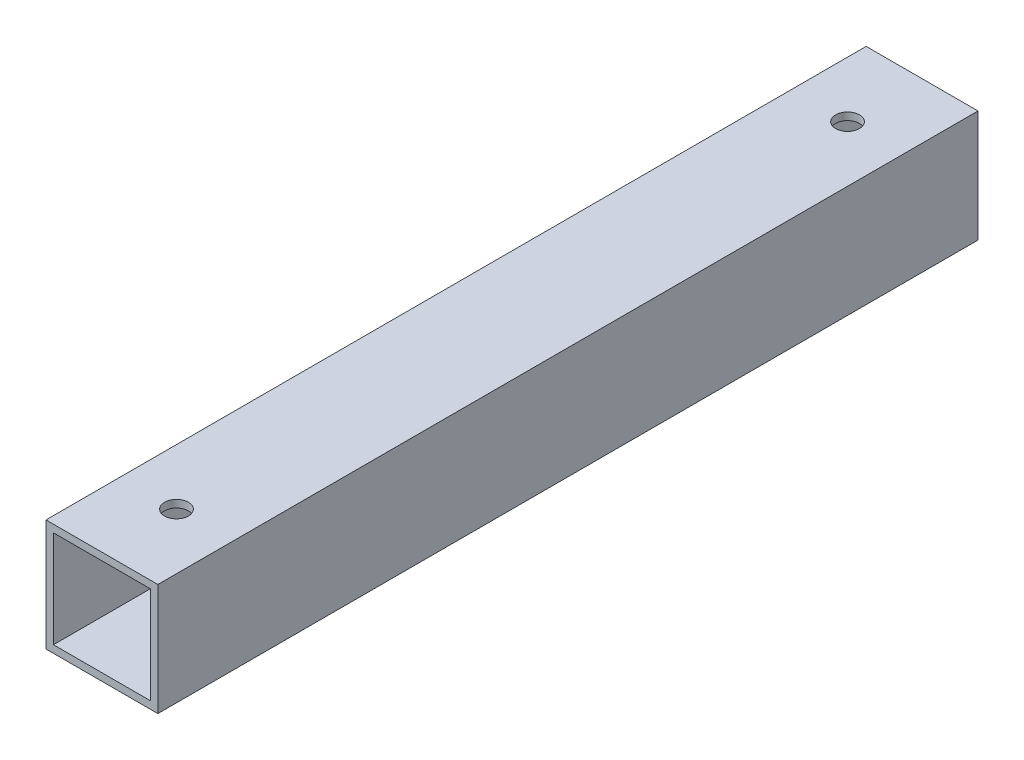
SolidWorks part; units mm, degrees
ref_plane "前视基准面" through (0, 0, 0) normal (0, 0, 1) x (1, 0, 0)
ref_plane "上视基准面" through (0, 0, 0) normal (0, 1, 0) x (1, 0, 0)
ref_plane "右视基准面" through (0, 0, 0) normal (1, 0, 0) x (0, 0, -1)
sketch "草图1" plane through (0, 0, 0) normal (0, 0, 1) x (1, 0, 0)
  line L1 (0, 0) -> (13, 0)
  line L2 (0, 0) -> (0, 13)
  line L3 (0, 13) -> (13, 13)
  line L4 (13, 0) -> (13, 13)
  dimension "D1" = 13
  dimension "D2" = 13
extrude "拉伸-薄壁1" add sketch "草图1" along normal blind 110 thin
sketch "草图2" plane through (0, 14, 0) normal (0, 1, 0) x (1, 0, 0)
  line L0 (14, -110) -> (-1, -110) construction
  line L1 (14, 0) -> (-1, 0) construction
  circle A0 centre (6.5, -10) radius 1.6
  circle A1 centre (6.5, -100) radius 1.6
  dimension "D1" = 3.2
  dimension "D2" = 10
  dimension "D3" = 10
  dimension "D4" = 3.2
extrude "切除-拉伸1" cut sketch "草图2" against normal blind 32
